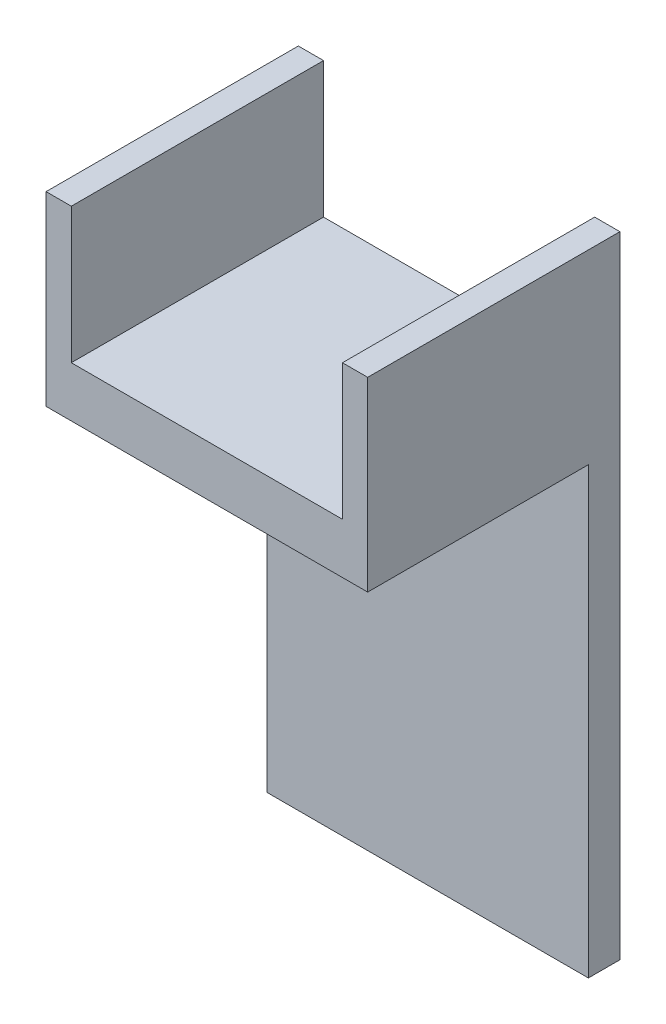
SolidWorks part; units mm, degrees
ref_plane "前视基准面" through (0, 0, 0) normal (0, 0, 1) x (1, 0, 0)
ref_plane "上视基准面" through (0, 0, 0) normal (0, 1, 0) x (1, 0, 0)
ref_plane "右视基准面" through (0, 0, 0) normal (1, 0, 0) x (0, 0, -1)
sketch "草图1" plane through (0, 0, 0) normal (0, 0, 1) x (1, 0, 0)
  line L5 (0, -100) -> (167.4067, -100)
  line L9 (167.4067, -100) -> (-167.4067, -100)
  arc A1 (-167.4067, -100) -> (167.4067, -100) centre (0, 0) ccw
  point P12 (0, 0)
extrude "凸台-拉伸1" add sketch "草图1" along normal blind 5 contours L9 A1 L5
sketch "草图4" plane through (0, 0, 5) normal (0, 0, 1) x (1, 0, 0)
  line L0 (0, 0) -> (0, -174.9432)
  line L1 (0, -100) -> (21.5, -100)
  line L2 (167.4067, -100) -> (-167.4067, -100) construction
  line L3 (0, -100) -> (-21.5, -100)
  line L4 (-21.5, -100) -> (-21.5, -121.5)
  line L5 (-21.5, -121.5) -> (21.5, -121.5)
  line L6 (21.5, -121.5) -> (21.5, -100)
  line L7 (0, 0) -> (167.4067, 0)
  line L8 (167.4067, 0) -> (167.4067, -100)
  line L9 (167.4067, -100) -> (-167.4067, -100)
  line L10 (-167.4067, -100) -> (-167.4067, 0)
  line L11 (-167.4067, 0) -> (0, 0)
  line M1 (167.4067, -100) -> (-167.4067, -100)
extrude "凸台-拉伸2" add sketch "草图4" against normal blind 5 contours L8 L7 L0 M1 | L11 L10 L0 M1
sketch "草图5" plane through (0, 0, 5) normal (0, 0, 1) x (1, 0, 0)
  line L0 (0, 0) -> (21.5, 0)
  line L1 (-167.4067, 0) -> (167.4067, 0) construction
  line L2 (0, 0) -> (-21.5, 0)
  line L3 (-21.5, 0) -> (-21.5, -21.5)
  line L4 (21.5, 0) -> (21.5, -21.5)
  line L5 (21.5, -21.5) -> (-21.5, -21.5)
extrude "切除-拉伸2" cut sketch "草图5" against normal blind 52
sketch "草图6" plane through (0, 0, 5) normal (0, 0, 1) x (1, 0, 0)
  line L0 (21.5, -21.5) -> (21.5, -29.5)
  line L1 (21.5, -29.5) -> (-21.5, -29.5)
  line L2 (-21.5, -29.5) -> (-21.5, -21.5)
  line L3 (-21.5, -21.5) -> (21.5, -21.5)
  line L4 (21.5, -29.5) -> (25.5, -29.5)
  line L5 (25.5, -29.5) -> (25.5, 0)
  line L6 (21.5, 0) -> (167.4067, 0) construction
  line L7 (25.5, 0) -> (21.5, 0)
  line L8 (21.5, 0) -> (21.5, -21.5)
  line L9 (-21.5, -29.5) -> (-25.5, -29.5)
  line L10 (-25.5, -29.5) -> (-25.5, 0)
  line L11 (-167.4067, 0) -> (-21.5, 0) construction
  line L12 (-25.5, 0) -> (-21.5, 0)
  line L13 (-21.5, 0) -> (-21.5, -21.5)
  line M1 (21.5, 0) -> (21.5, -21.5)
  line M2 (21.5, -21.5) -> (-21.5, -21.5)
  line M3 (-21.5, -21.5) -> (-21.5, 0)
  line M4 (-21.5, 0) -> (-167.4067, 0)
  line M8 (167.4067, 0) -> (21.5, 0)
extrude "凸台-拉伸3" add sketch "草图6" along normal blind 35 contours L10 L9 L2 M3 M4 | L2 L1 L0 M2 | L4 L5 L0 M8 M1
sketch "草图8" plane through (0, 0, 0) normal (1, 0, 0) x (0, 0, -1)
  line L0 (-40, -29.5) -> (-5, -50)
  line L3 (-5, 0) -> (-5, -100) construction
rib "筋4" sketch "草图8" sketch "草图8" thickness 10 extrusion direction parallel to sketch draft on no parameters "D1"=10
sketch "草图9" plane through (0, 0, 0) normal (0, 0, -1) x (-1, 0, 0)
  line L0 (-167.4067, -100) -> (167.4067, -100)
  line L1 (167.4067, -100) -> (167.4067, -206.3687)
  line L2 (167.4067, -206.3687) -> (-177.6885, -206.3687)
  line L3 (-177.6885, -206.3687) -> (-167.4067, -100)
extrude "切除-拉伸3" cut sketch "草图9" against normal blind 35
sketch "草图10" plane through (0, 0, 0) normal (0, 0, -1) x (-1, 0, 0)
  line L0 (-21.5, 0) -> (-25.5, 0)
  line L1 (-21.5, 0) -> (-167.4067, 0) construction
  line L2 (-25.5, 0) -> (-25.5, -100)
  line L3 (167.4067, -100) -> (-167.4067, -100) construction
  line L4 (21.5, 0) -> (25.5, 0)
  line L5 (167.4067, 0) -> (21.5, 0) construction
  line L6 (25.5, 0) -> (25.5, -100)
  line L7 (25.5, -100) -> (-25.5, -100)
  line L8 (-167.4067, -100) -> (-25.5, -100)
  line L9 (-25.5, 0) -> (-167.4067, 0)
  line L10 (-167.4067, 0) -> (-167.4067, -100)
  line L11 (25.5, -100) -> (167.4067, -100)
  line L12 (167.4067, -100) -> (167.4067, 0)
  line L13 (167.4067, 0) -> (25.5, 0)
  line M2 (-167.4067, 0) -> (-167.4067, -100)
  line M3 (-167.4067, -100) -> (167.4067, -100)
  line M4 (167.4067, -100) -> (167.4067, 0)
  line M5 (167.4067, 0) -> (21.5, 0)
  line M9 (-21.5, 0) -> (-167.4067, 0)
extrude "切除-拉伸4" cut sketch "草图10" against normal blind 10 contours L2 M9 M2 M3 | L6 M5 M3 M4
